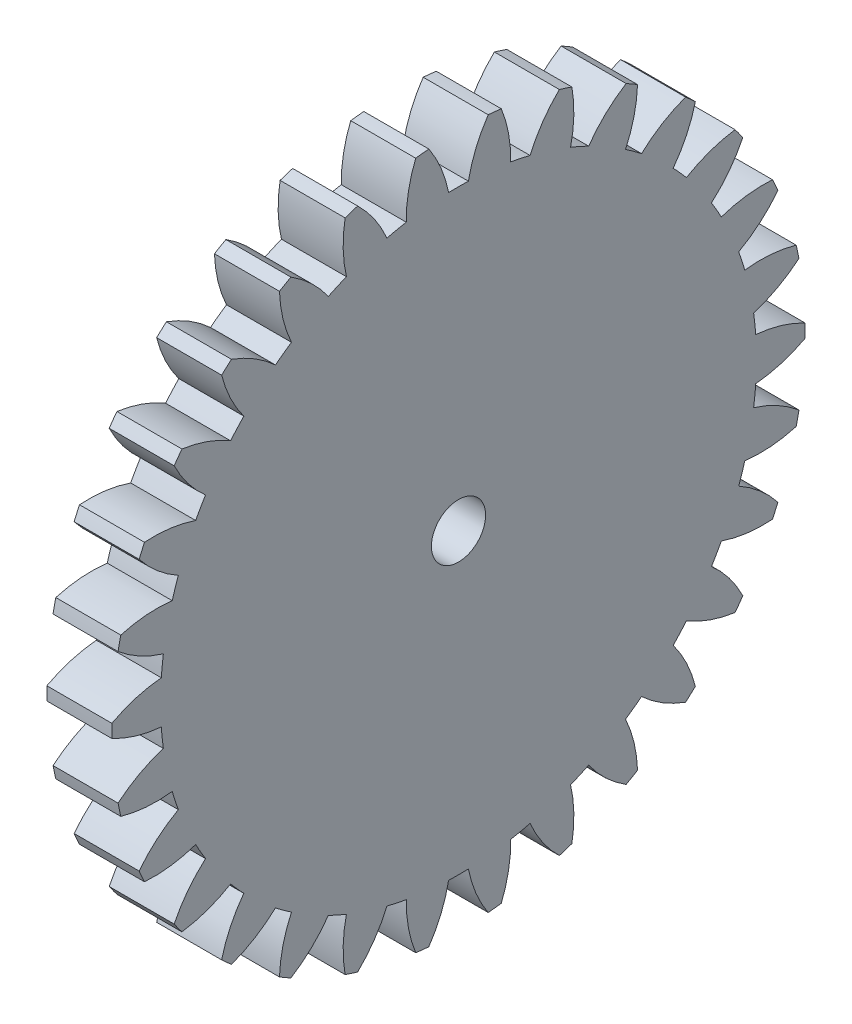
SolidWorks part; units mm, degrees
ref_plane "Plane1" through (0, 0, 0) normal (0, 0, 1) x (1, 0, 0)
ref_plane "Plane2" through (0, 0, 0) normal (0, 1, 0) x (1, 0, 0)
ref_plane "Plane3" through (0, 0, 0) normal (1, 0, 0) x (0, 0, -1)
sketch "HoldingSke" plane through (0, 0, 0) normal (0, 1, 0) x (1, 0, 0)
  line L0 (0, 0) -> (0.2165, -0.125)
  line L1 (-15, 0) -> (100, 0) construction
  line L2 (0, 0) -> (-2.1039, 2.3779)
  line L3 (0, 0) -> (-11.863, 4.5341)
  line L4 (0, 0) -> (7.479, 4.318)
  line L5 (0, 0) -> (-46.8476, -17.4728)
  line L6 (0, 0) -> (-9.9476, -6.7116)
  line L7 (-2.1039, 2.3779) -> (8.6586, 51.2059)
  line L8 (-76.2, 54.61) -> (-74.4, 54.61)
  line L9 (-71.009, 38.7566) -> (-53.1078, 45.2721)
  line L10 (-76.2, 71.12) -> (104.1128, 71.12)
  line L11 (0, 0) -> (-12, 0)
  line L12 (-76.2, 101.6) -> (-76.073, 101.6)
  line L13 (24.9733, 27.94) -> (52.9518, 28.4284)
  line L14 (24.9733, 27.94) -> (24.9743, 27.94)
  line L15 (24.9733, 27.94) -> (100.4006, 29.5858)
  line L16 (-63.627, -4) -> (-12.827, -4)
  circle A0 centre (0, 0) radius 5
  circle A1 centre (0, 0) radius 37.5
  circle A2 centre (0, 0) radius 37.5
  circle A3 centre (0, 0) radius 5
  dimension "MHD" = 75
  dimension "Hub_dia" = 75
  dimension "Bore" = 10
  dimension "MBD" = 10
  dimension "Num_teeth" = 30
  dimension "Pitch" = 0.25
  dimension "Overall_len" = 50
  dimension "Show_teeth" = 30
  dimension "Thickness" = 12
  dimension "OAL" = 50.0001
  dimension "T_dim" = 1.8
  dimension "Ap" = 20
  dimension "H" = 19.05
  dimension "Pitch_radius" = 180.3128
  dimension "Width" = 12
  dimension "Backlash" = 0.127
  dimension "Addendum_fac" = 1
  dimension "Dedendum_fac" = 1.25
  dimension "Clearance_fac" = 0.25
  dimension "Dedendum_add" = 0.001
  dimension "Module" = 4
sketch "BasProSke" plane through (0, 0, 0) normal (0, 1, 0) x (1, 0, 0)
  line L0 (-10, 0) -> (60, 0) construction
  line L1 (0, 0) -> (0, 64)
  line L2 (0, 0) -> (12, 0)
  line L3 (12, 0) -> (12, 64)
  line L4 (12, 64) -> (0, 64)
  dimension "Thickness" = 12
  dimension "Diameter" = 128
revolve "Base-Revolve" add sketch "BasProSke" angle 360 about L0
sketch "TooCutSke" plane through (0, 0, 0) normal (1, 0, 0) x (0, 0, -1)
  line L1 (0, 0) -> (0, 107) construction
  line L2 (0, 0) -> (-3.3624, 59.9057) construction
  line L3 (0, 0) -> (-12.5286, 119.2014) construction
  line L4 (-3.3624, 59.9057) -> (-6.2643, 59.6007) construction
  arc A0 (1.8261, 54.9687) -> (-1.8261, 54.9687) centre (0, 0) ccw
  arc A1 (5.4942, 63.7892) -> (-5.4942, 63.7892) centre (0, 0) ccw
  circle A2 centre (0, 0) radius 60 construction
  circle A3 centre (0, 0) radius 56.3816 construction
  arc A4 (-1.8261, 54.9687) -> (-5.4942, 63.7892) centre (-25.377, 50.3477) ccw
  arc A5 (5.4942, 63.7892) -> (1.8261, 54.9687) centre (25.377, 50.3477) ccw
  dimension "Root_dia" = 109.998
  dimension "Overcut_dia" = 128.0508
  dimension "Pitch_dia" = 120
  dimension "Base_dia" = 112.7631
  dimension "Flank_rad" = 24
  dimension "Half_ang" = 6
  dimension "Half_CT" = 2.9179
extrude "ToothCut" cut sketch "TooCutSke" along normal through all
fillet "Breaks" [suppressed] radius 0.08
fillet "RootFillets" [suppressed] radius 1.001
pattern_circular "TeethCuts" count 30 every 12 about axis through (-10, 0, 0) along (1, 0, 0) of "ToothCut", "RootFillets", "Breaks"
sketch "HubNeaOneSke" plane through (0, 0, 0) normal (-1, 0, 0) x (0, 0, 1)
  circle A0 centre (0, 0) radius 37.5
  dimension "Diameter" = 75
extrude "HubNearOne" [suppressed] add sketch "HubNeaOneSke" along normal blind 38.0001
sketch "HubNeaBotSke" plane through (0, 0, 0) normal (-1, 0, 0) x (0, 0, 1)
  circle A0 centre (0, 0) radius 37.5
  dimension "Diameter" = 75
extrude "HubNearBoth" [suppressed] add sketch "HubNeaBotSke" along normal blind 19
ref_plane "FarPln" through (12, 0, 0) normal (1, 0, 0) x (0, 0, -1)
sketch "HubFarSke" plane through (12, 0, 0) normal (1, 0, 0) x (0, 0, -1)
  circle A0 centre (0, 0) radius 37.5
  dimension "Diameter" = 75
extrude "HubFar" [suppressed] add sketch "HubFarSke" along normal blind 19
sketch "BorSke" plane through (0, 0, 0) normal (1, 0, 0) x (0, 0, -1)
  circle A0 centre (0, 0) radius 5
  dimension "Diameter" = 10
extrude "Bore" cut sketch "BorSke" along normal mid plane 100.0001
sketch "KeySke" plane through (0, 0, 0) normal (1, 0, 0) x (0, 0, -1)
  line L0 (-2, 0) -> (-2, 6.8)
  line L1 (-2, 6.8) -> (2, 6.8)
  line L2 (2, 6.8) -> (2, 0)
  line L3 (0, 0) -> (0, 34) construction
  line L4 (-2, 0) -> (2, 0)
  dimension "Offset" = 6.8
  dimension "Width" = 4
extrude "Keyway" [suppressed] cut sketch "KeySke" along normal mid plane 100.0001
pattern_circular "Keyway2" [suppressed] count 2 every 90 about axis through (-10, 0, 0) along (1, 0, 0)
equation "' \"Module@HoldingSke\" = 6.35"
equation "' \"Num_teeth@HoldingSke\" = 12"
equation "' \"Ap@HoldingSke\" =  20"
equation "' \"Ap@HoldingSke\" = 20"
equation "' \"Width@HoldingSke\" = 0.5 * 25.4"
equation "' \"Hub_dia@HoldingSke\"= 1 * 25.4"
equation "' \"Hub_dia@HoldingSke\" = 1 * 25.4"
equation "' \"Overall_len@HoldingSke\" = 1.0 * 25.4"
equation "' \"Bore@HoldingSke\" = 0.75 * 25.4"
equation "' \"T_dim@HoldingSke\" = 0.1 * 25.4"
equation "' \"Width@KeySke\" = 0.25 * 25.4"
equation "' \"Show_teeth@HoldingSke\" = 13"
equation "' \"Backlash@HoldingSke\" = 0.009 * 25.4"
equation "' \"Addendum_fac@HoldingSke\" = 1.0"
equation "' \"Dedendum_fac@HoldingSke\" = 1.25"
equation "' \"Dedendum_add@HoldingSke\" = 0.00005 * 25.4"
equation "' \"Clearance_fac@HoldingSke\" = 0.25"
equation "\"Pitch@HoldingSke\" = 1 / \"Module@HoldingSke\""
equation "\"Overcut_dia@TooCutSke\" = (\"Num_teeth@HoldingSke\" + 2 * \"Addendum_fac@HoldingSke\") / \"Pitch@HoldingSke\" + 0.002 * 25.4"
equation "\"Pitch_dia@TooCutSke\" = \"Num_teeth@HoldingSke\" / \"Pitch@HoldingSke\""
equation "\"Base_dia@TooCutSke\" = \"Num_teeth@HoldingSke\" / \"Pitch@HoldingSke\" * cos((\"Ap@HoldingSke\"  * 3.14159265 / 180))"
equation "\"Root_dia@TooCutSke\" = (\"Num_teeth@HoldingSke\" + 2) / \"Pitch@HoldingSke\" - 2 * (\"Addendum_fac@HoldingSke\" + \"Dedendum_fac@HoldingSke\") / \"Pitch@HoldingSke\" - \"Dedendum_add@HoldingSke\" * 2"
equation "\"Half_ang@TooCutSke\" = 180 / \"Num_teeth@HoldingSke\""
equation "\"Half_CT@TooCutSke\" = \"Num_teeth@HoldingSke\" / \"Pitch@HoldingSke\" * sin((3.14159265 / 2 / \"Num_teeth@HoldingSke\")) / 2 - 7 * \"Backlash@HoldingSke\" / 4"
equation "\"Flank_rad@TooCutSke\" = \"Num_teeth@HoldingSke\" / \"Pitch@HoldingSke\" / 5"
equation "\"Radius@RootFillets\" = \"Clearance_fac@HoldingSke\" / \"Pitch@HoldingSke\" + \"Dedendum_add@HoldingSke\""
equation "\"Break_rad@Breaks\" = 0.02 / \"Pitch@HoldingSke\""
equation "\"Thickness@HoldingSke\" = \"Width@HoldingSke\""
equation "\"OAL@HoldingSke\" = \"Thickness@HoldingSke\""
equation "\"MHD@HoldingSke\" = (\"Num_teeth@HoldingSke\" + 2) / \"Pitch@HoldingSke\" - 2 * (\"Addendum_fac@HoldingSke\" + \"Dedendum_fac@HoldingSke\")  / \"Pitch@HoldingSke\" - \"Dedendum_add@HoldingSke\" * 2"
equation "\"MBD@HoldingSke\" = (\"Num_teeth@HoldingSke\" + 2) / \"Pitch@HoldingSke\" - 2 * (\"Addendum_fac@HoldingSke\" + \"Dedendum_fac@HoldingSke\")  / \"Pitch@HoldingSke\" - \"Dedendum_add@HoldingSke\" * 2 - 0.002 * 25.4"
equation "\"MHD@HoldingSke\" = ((sgn( \"MHD@HoldingSke\" - \"Hub_dia@HoldingSke\" )-1)*( \"MHD@HoldingSke\" - \"Hub_dia@HoldingSke\" ))/-2+ \"Hub_dia@HoldingSke\""
equation "\"MBD@HoldingSke\" = ((sgn( \"MBD@HoldingSke\" - \"Bore@HoldingSke\" )-1)*( \"MBD@HoldingSke\" - \"Bore@HoldingSke\" ))/-2+ \"Bore@HoldingSke\""
equation "\"OAL@HoldingSke\" = ((sgn( \"OAL@HoldingSke\" - \"Overall_len@HoldingSke\" )+1)*( \"OAL@HoldingSke\" - \"Overall_len@HoldingSke\" ))/2 + \"Overall_len@HoldingSke\" + 0.000002 * 25.4"
equation "\"Num_teeth@TeethCuts\" = int( \"Show_teeth@HoldingSke\" ) + 1"
equation "\"Num_teeth@TeethCuts\" = ((sgn( \"Num_teeth@TeethCuts\" - \"Num_teeth@HoldingSke\" )-1)*( \"Num_teeth@TeethCuts\" - \"Num_teeth@HoldingSke\" ))/-2+ \"Num_teeth@HoldingSke\""
equation "\"Num_teeth@TeethCuts\" = ((sgn( \"Num_teeth@TeethCuts\" - 2.0)+1)*( \"Num_teeth@TeethCuts\" - 2.0))/2 +2.0"
equation "\"Angle@TeethCuts\" = 360.0 / \"Num_teeth@HoldingSke\""
equation "\"Diameter@BasProSke\" = (\"Num_teeth@HoldingSke\" + 2 * \"Addendum_fac@HoldingSke\") / \"Pitch@HoldingSke\""
equation "\"Thickness@BasProSke\"  = \"Thickness@HoldingSke\""
equation "' \"Fillet_rad@BasProSke\" =  \"Thickness@HoldingSke\" * 0.05"
equation "' \"Fillet_rad@BasProSke\" = \"Thickness@HoldingSke\" * 0.05"
equation "\"MHD@HoldingSke\" = ((sgn( \"MHD@HoldingSke\" - \"Root_dia@TooCutSke\" )-1)*( \"MHD@HoldingSke\" - \"Root_dia@TooCutSke\" ))/-2+ \"Root_dia@TooCutSke\""
equation "\"Diameter@HubNeaOneSke\" = \"MHD@HoldingSke\""
equation "\"Length@HubNearOne\" = \"OAL@HoldingSke\" - \"Thickness@BasProSke\""
equation "\"Diameter@HubNeaBotSke\" = \"MHD@HoldingSke\""
equation "\"Length@HubNearBoth\" = ( \"OAL@HoldingSke\" - \"Thickness@BasProSke\" ) / 2.0"
equation "\"Thickness@FarPln\" = \"Thickness@BasProSke\""
equation "\"Diameter@HubFarSke\" = \"MHD@HoldingSke\""
equation "\"Length@HubFar\" = ( \"OAL@HoldingSke\" - \"Thickness@BasProSke\" ) / 2.0"
equation "\"Diameter@BorSke\" = \"MBD@HoldingSke\""
equation "\"D1@Bore\" = \"OAL@HoldingSke\" * 2.0"
equation "\"D1@Keyway\" = \"OAL@HoldingSke\" * 2.0"
equation "\"Offset@KeySke\" = \"T_dim@HoldingSke\" + \"MBD@HoldingSke\" / 2.0"
